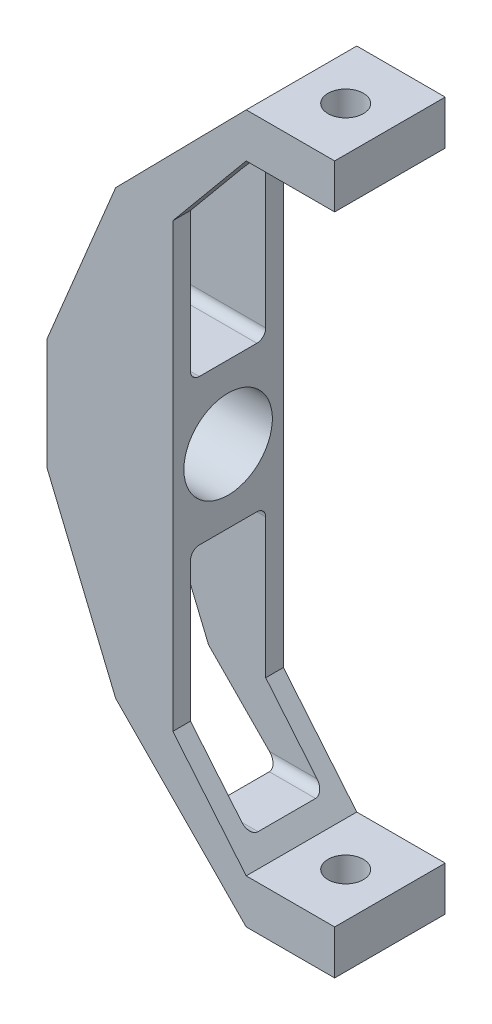
SolidWorks part; units mm, degrees
ref_plane "Front Plane" through (0, 0, 0) normal (0, 0, 1) x (1, 0, 0)
ref_plane "Top Plane" through (0, 0, 0) normal (0, 1, 0) x (1, 0, 0)
ref_plane "Right Plane" through (0, 0, 0) normal (1, 0, 0) x (0, 0, -1)
sketch "Sketch1" plane through (0, 0, 0) normal (0, 0, 1) x (1, 0, 0)
  line L0 (0, 0) -> (-20, 0)
  line L2 (-20, -160) -> (0, -160)
  line L3 (0, -160) -> (0, -150)
  line L4 (0, -150) -> (-20, -150)
  line L5 (-36.59, -130) -> (-36.59, -30)
  line L6 (-20, -10) -> (0, -10)
  line L7 (0, -10) -> (0, 0)
  line L13 (-10, 0) -> (-10, -160) construction
  line L14 (-49.5183, -30) -> (-65.09, -67.5)
  line L15 (-65.09, -67.5) -> (-65.09, -92.5)
  line L16 (-65.09, -92.5) -> (-49.5183, -130)
  line L17 (-36.59, -30) -> (-20, -10)
  line L18 (-36.59, -130) -> (-20, -150)
  line L19 (-36.59, -30) -> (-49.5183, -30) construction
  line L20 (-49.5183, -30) -> (-20, 0)
  line L21 (-36.59, -130) -> (-49.5183, -130) construction
  line L22 (-49.5183, -130) -> (-20, -160)
  point P4 (-36.59, -80)
  point P8 (-65.09, -80)
  point P14 (-10, -80)
  dimension "D8" = 100
  dimension "D1" = 26.59
  dimension "D2" = 140
  dimension "D3" = 10
  dimension "D5" = 10
  dimension "D6" = 10
  dimension "D7" = 10
  dimension "D9" = 28.5
  dimension "D10" = 25
  dimension "D11" = 10
  dimension "D12" = 10
extrude "Boss-Extrude1" add sketch "Sketch1" along normal blind 25
sketch "Sketch3" plane through (-65.09, 0, 0) normal (-1, 0, 0) x (0, 0, 1)
  line L1 (6, -63.5) -> (19, -63.5)
  line L2 (4, -61.5) -> (4, -15.9991)
  line L3 (6, -13.9991) -> (19, -13.9991)
  line L4 (21, -61.5) -> (21, -15.9991)
  line L6 (25, -30) -> (25, -67.5) construction
  line L7 (0, -30) -> (0, -67.5) construction
  line L8 (25, -67.5) -> (0, -67.5) construction
  line L9 (0, -80) -> (25, -80) construction
  line L10 (0, -67.5) -> (0, -92.5) construction
  line L11 (25, -67.5) -> (25, -92.5) construction
  line L12 (6, -146.0009) -> (19, -146.0009)
  line L13 (21, -98.5) -> (21, -144.0009)
  line L14 (6, -96.5) -> (19, -96.5)
  line L15 (4, -98.5) -> (4, -144.0009)
  arc A0 (6, -63.5) -> (4, -61.5) centre (6, -61.5) cw
  arc A1 (19, -63.5) -> (21, -61.5) centre (19, -61.5) ccw
  arc A2 (19, -13.9991) -> (21, -15.9991) centre (19, -15.9991) cw
  arc A3 (4, -15.9991) -> (6, -13.9991) centre (6, -15.9991) cw
  arc A4 (19, -146.0009) -> (21, -144.0009) centre (19, -144.0009) ccw
  arc A5 (19, -96.5) -> (21, -98.5) centre (19, -98.5) cw
  arc A6 (6, -96.5) -> (4, -98.5) centre (6, -98.5) ccw
  arc A7 (4, -144.0009) -> (6, -146.0009) centre (6, -144.0009) ccw
  circle A8 centre (12.5, -80) radius 10
  dimension "D5" = 2
  dimension "D6" = 20
  dimension "D2" = 4
  dimension "D3" = 4
  dimension "D4" = 4
extrude "Cut-Extrude2" cut sketch "Sketch3" against normal through all
sketch "Sketch4" plane through (0, 0, 0) normal (0, 1, 0) x (1, 0, 0)
  line L0 (-10, 0) -> (-10, -25) construction
  line L1 (0, 0) -> (-20, 0) construction
  line L2 (0, -25) -> (-20, -25) construction
  line L3 (-36.59, -25) -> (-36.59, -21) construction
  circle A0 centre (-10, -12.5) radius 4
  dimension "D2" = 8
  dimension "D1" = 26.59
extrude "Cut-Extrude3" cut sketch "Sketch4" against normal through all
